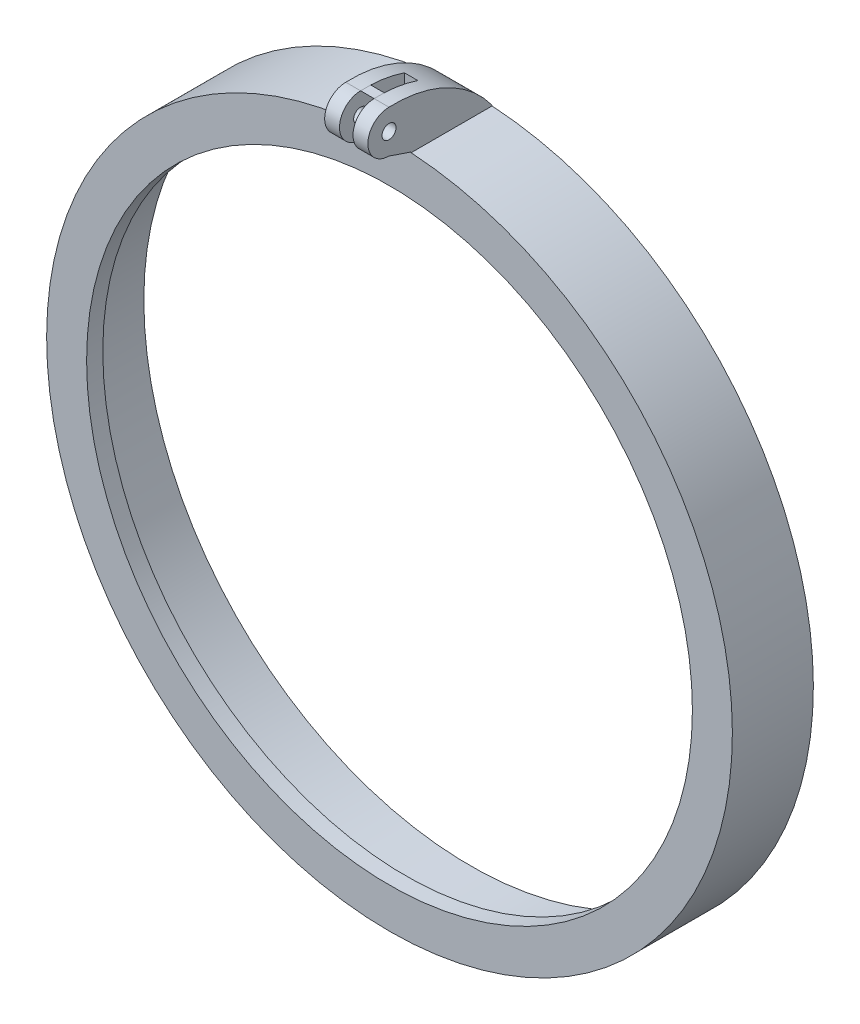
SolidWorks part; units mm, degrees
ref_plane "Front Plane" through (0, 0, 0) normal (0, 0, 1) x (1, 0, 0)
ref_plane "Top Plane" through (0, 0, 0) normal (0, 1, 0) x (1, 0, 0)
ref_plane "Right Plane" through (0, 0, 0) normal (1, 0, 0) x (0, 0, -1)
sketch "Sketch1" plane through (0, 0, 0) normal (0, 0, 1) x (1, 0, 0)
  circle A0 centre (0, 0) radius 63.5
  dimension "D1" = 127
extrude "Boss-Extrude2" add sketch "Sketch1" along normal blind 15
shell "Shell4" thickness 3
sketch "Sketch4" plane through (0, 0, 12) normal (0, 0, -1) x (-1, 0, 0)
  circle A0 centre (0, 0) radius 56.097
extrude "Cut-Extrude1" cut sketch "Sketch4" against normal blind 22
sketch "Sketch8" plane through (0, 0, 0) normal (1, 0, 0) x (0, 0, -1)
  line L0 (-15, 63.5) -> (0, 63.5)
  arc A0 (-19.0928, 72.7285) -> (-19.0928, 64.8949) centre (-19.0928, 68.8117) ccw
  circle A1 centre (-19.0928, 68.8117) radius 1.3
  arc A2 (-19.0928, 72.7285) -> (0, 63.5) centre (-18.1616, 50.2902) cw
  arc A3 (-19.0928, 64.8949) -> (-15, 63.5) centre (39.1844, 229.1859) ccw
  dimension "D1" = 2.6
extrude "Boss-Extrude6" add sketch "Sketch8" along normal blind 4 and the other way blind 4 separate body
sketch "Sketch9" plane through (0, 63.5, 0) normal (0, -1, 0) x (1, 0, 0)
  line L1 (-4, 15) -> (4, 15)
  line L2 (-4, 15) -> (-4, 0)
  line L3 (-4, 0) -> (4, 0)
  line L4 (4, 15) -> (4, 0)
extrude "Boss-Extrude7" add sketch "Sketch9" along normal up to surface up to face at (63.5, 0, 15)
sketch "Sketch10" plane through (0, 0, 15) normal (0, 0, 1) x (1, 0, 0)
  line L0 (4, 63.5) -> (-4, 63.5) construction
  line L1 (-1.25, 63.5) -> (1.25, 63.5)
  line L2 (-1.25, 63.5) -> (-1.25, 72.7285)
  line L3 (-1.25, 72.7285) -> (1.25, 72.7285)
  line L4 (1.25, 63.5) -> (1.25, 72.7285)
  line L5 (-4, 72.7285) -> (4, 72.7285) construction
  line L6 (-4, 72.7285) -> (-4, 64.8949) construction
  dimension "D1" = 2.5
  dimension "D2" = 2.75
extrude "Cut-Extrude2" cut sketch "Sketch10" along normal blind 9 and the other way blind 4
